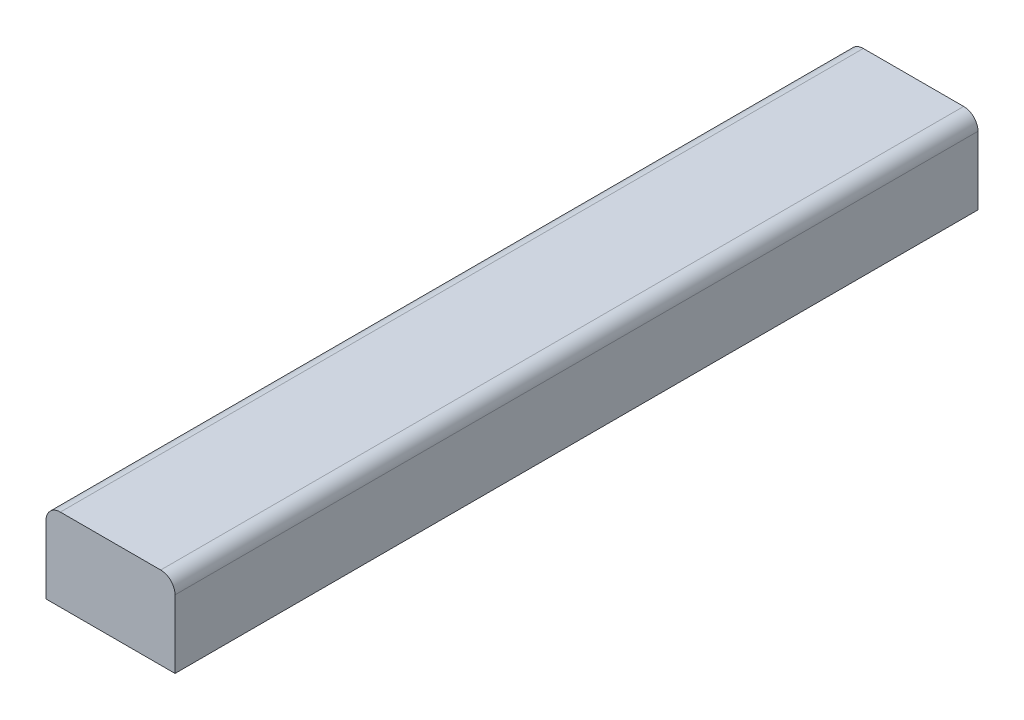
SolidWorks part; units mm, degrees
ref_plane "Front Plane" through (0, 0, 0) normal (1, 0, 0) x (0, 1, 0)
ref_plane "Top Plane" through (0, 0, 0) normal (0, 0, 1) x (0, 1, 0)
ref_plane "Right Plane" through (0, 0, 0) normal (0, 1, 0) x (-1, 0, 0)
sketch "Sketch1" plane through (0, 0, 0) normal (0, 0, 1) x (0, 1, 0)
  line L1 (-36.5125, -57.15) -> (36.5125, -57.15)
  line L2 (-36.5125, -57.15) -> (-36.5125, 57.15)
  line L3 (-36.5125, 57.15) -> (36.5125, 57.15)
  line L4 (36.5125, -57.15) -> (36.5125, 57.15)
  line L5 (-36.5125, -57.15) -> (36.5125, 57.15) construction
  line L6 (-36.5125, 57.15) -> (36.5125, -57.15) construction
  point P0 (0, 0)
  dimension "D1" = 73.025
  dimension "D2" = 114.3
extrude "Boss-Extrude1" add sketch "Sketch1" along normal blind 711.2
sketch "Sketch2" plane through (0, 36.5125, 0) normal (0, 1, 0) x (-1, 0, 0)
  line L0 (0, 711.2) -> (0, 0) construction
  line L1 (-57.15, 711.2) -> (57.15, 711.2) construction
fillet "Fillet1" radius 12.7 2 edges at (-57.15, 36.5125, 355.6) (57.15, 36.5125, 355.6)
